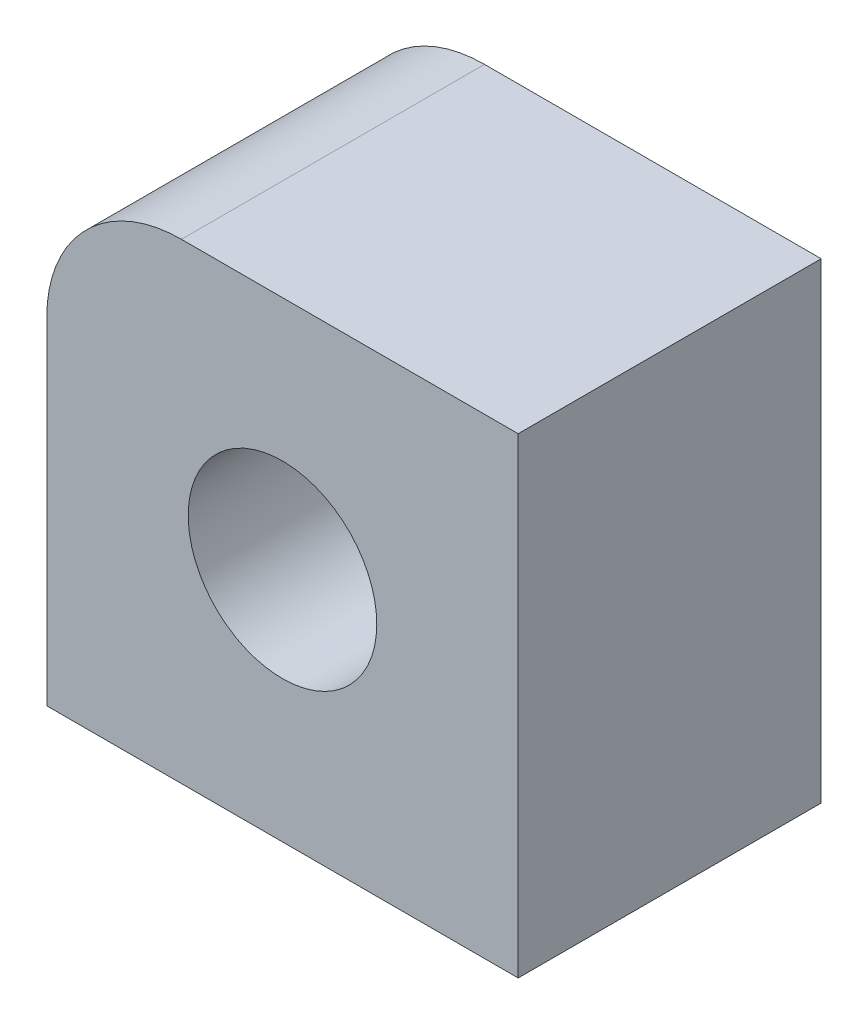
SolidWorks part; units mm, degrees
ref_plane "Front Plane" through (0, 0, 0) normal (0, 0, 1) x (1, 0, 0)
ref_plane "Top Plane" through (0, 0, 0) normal (0, 1, 0) x (1, 0, 0)
ref_plane "Right Plane" through (0, 0, 0) normal (1, 0, 0) x (0, 0, -1)
sketch "Sketch1" plane through (0, 0, 0) normal (0, 0, 1) x (1, 0, 0)
  line L1 (3.5, -3.5) -> (-3.5, -3.5)
  line L2 (3.5, -3.5) -> (3.5, 3.5)
  line L3 (3.5, 3.5) -> (-3.5, 3.5)
  line L4 (-3.5, -3.5) -> (-3.5, 3.5)
  line L5 (3.5, -3.5) -> (-3.5, 3.5) construction
  line L6 (3.5, 3.5) -> (-3.5, -3.5) construction
  point P0 (0, 0)
  dimension "D1" = 7
  dimension "D2" = 7
extrude "Boss-Extrude1" add sketch "Sketch1" along normal blind 4.5
sketch "Sketch2" plane through (0, 0, 4.5) normal (0, 0, 1) x (1, 0, 0)
  circle A0 centre (0, 0) radius 1.4
  dimension "D1" = 2.8
extrude "Cut-Extrude1" cut sketch "Sketch2" against normal through all
fillet "Fillet1" radius 2 1 edges at (-3.5, 3.5, 2.25)
